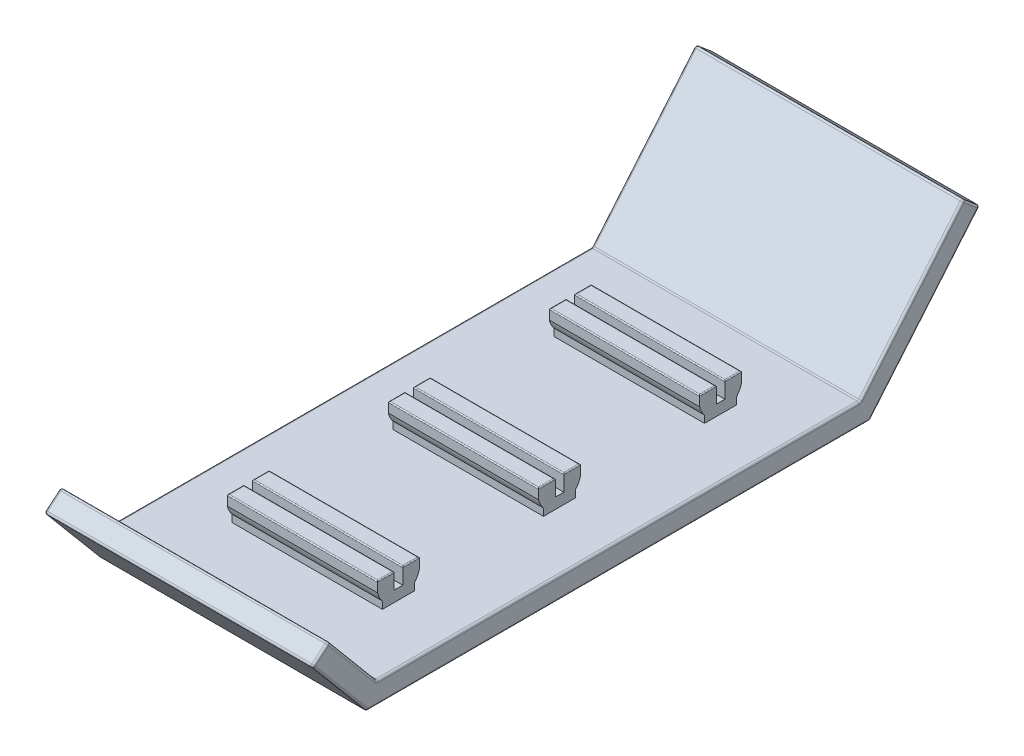
SolidWorks part; units mm, degrees
ref_plane "前视基准面" through (0, 0, 0) normal (0, 0, 1) x (1, 0, 0)
ref_plane "上视基准面" through (0, 0, 0) normal (0, 1, 0) x (1, 0, 0)
ref_plane "右视基准面" through (0, 0, 0) normal (1, 0, 0) x (0, 0, -1)
sketch "草图1" plane through (0, 0, 0) normal (1, 0, 0) x (0, 0, -1)
  line L0 (0, 0) -> (-7.5, 0)
  line L1 (-7.5, 0) -> (-11.9995, 5.3623)
  line L2 (0, 0) -> (37.5, 0)
  line L3 (37.5, 0) -> (47.1418, 11.4907)
  line L4 (-8.4326, -2) -> (-13.5316, 4.0767)
  line L5 (0, -2) -> (-8.4326, -2)
  line L6 (0, -2) -> (38.4326, -2)
  line L7 (38.4326, -2) -> (48.6739, 10.2051)
  line L8 (-11.9995, 5.3623) -> (-13.5316, 4.0767)
  line L9 (47.1418, 11.4907) -> (48.6739, 10.2051)
  dimension "D1" = 7.5
  dimension "D2" = 37.5
  dimension "D3" = 130
  dimension "D4" = 130
  dimension "D5" = 7
  dimension "D6" = 15
  dimension "D7" = 2
extrude "凸台-拉伸1" add sketch "草图1" along normal blind 25
sketch "草图2" plane through (25, 0, 0) normal (1, 0, 0) x (0, 0, -1)
  line L0 (0, 0) -> (0, 2) construction
  line L1 (0, 2) -> (0, 2.5) construction
  line L2 (1.5, 0) -> (-1.5, 0)
  line L3 (37.5, 0) -> (-7.5, 0) construction
  line L4 (-1.5, 0) -> (-1.5, 0.6771)
  line L5 (-0.4, 2.5) -> (-1.95, 2.5)
  line L6 (-1.95, 2.5) -> (-1.95, 1.5556)
  line L7 (0.4, 1) -> (-0.4, 1)
  line L8 (-0.4, 1) -> (-0.4, 2.5)
  line L9 (0, 2.5) -> (-0.4, 2.5) construction
  line L10 (1.5, 0) -> (1.5, 0.6771)
  line L11 (1.95, 2.5) -> (1.95, 1.5556)
  line L12 (0.4, 2.5) -> (1.95, 2.5)
  line L13 (0.4, 1) -> (0.4, 2.5)
  arc A0 (-1.95, 1.5556) -> (-1.5, 0.6771) centre (0, 2) ccw
  arc A1 (1.95, 1.5556) -> (1.5, 0.6771) centre (0, 2) cw
  point P19 (0, 1)
  dimension "D1" = 2
  dimension "D2" = 0.5
  dimension "D3" = 1.5
  dimension "D4" = 1.95
  dimension "D5" = 1
  dimension "D6" = 0.4
extrude "凸台-拉伸2" add sketch "草图2" against normal blind 14 from offset 5.5 offset against normal yes
pattern_linear "阵列(线性)1" count 3 spacing 15 along (0, 0, -1) of "凸台-拉伸2"
fillet "圆角1" radius 0.1 24 edges at (12.5, 2.5, -30.4) (5.5, 2.5, -31.175) (12.5, 2.5, -31.95) (19.5, 2.5, -31.175) (12.5, 2.5, -28.05) (5.5, 2.5, -28.825) (12.5, 2.5, -29.6) (19.5, 2.5, -28.825) (12.5, 2.5, -15.4) (5.5, 2.5, -16.175) (12.5, 2.5, -16.95) (19.5, 2.5, -16.175) (12.5, 2.5, -13.05) (5.5, 2.5, -13.825) (12.5, 2.5, -14.6) (19.5, 2.5, -13.825) (12.5, 2.5, -0.4) (5.5, 2.5, -1.175) (12.5, 2.5, -1.95) (19.5, 2.5, -1.175) (12.5, 2.5, 1.95) (5.5, 2.5, 1.175) (12.5, 2.5, 0.4) (19.5, 2.5, 1.175)
fillet "圆角2" radius 0.2 24 edges at (12.5, 10.2051, -48.6739) (12.5, 11.4907, -47.1418) (0, 2.6812, 9.7498) (0, 1.0384, 10.9821) (0, -2, -15) (0, 4.1025, -43.5533) (0, 10.8479, -47.9079) (0, 5.7453, -42.3209) (0, 0, -15) (12.5, 5.3623, 11.9995) (12.5, 4.0767, 13.5316) (0, 4.7195, 12.7656) (25, 5.7453, -42.3209) (25, 10.8479, -47.9079) (25, 4.1025, -43.5533) (25, -2, -15) (25, 1.0384, 10.9821) (25, 4.7195, 12.7656) (25, 2.6812, 9.7498) (25, 0, -15) (12.5, -2, 8.4326) (12.5, -2, -38.4326) (12.5, 0, 7.5) (12.5, 0, -37.5)
